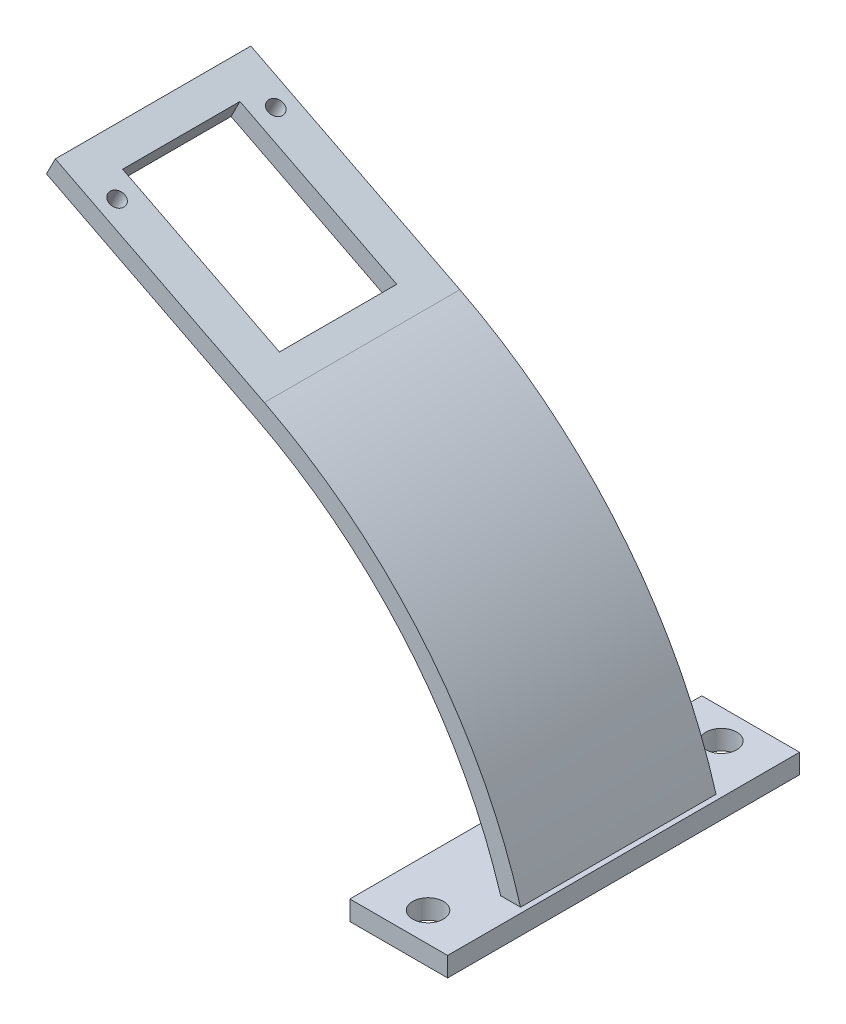
SolidWorks part; units mm, degrees
ref_plane "Front" through (0, 0, 0) normal (0, 0, 1) x (1, 0, 0)
ref_plane "Top" through (0, 0, 0) normal (0, 1, 0) x (1, 0, 0)
ref_plane "Right" through (0, 0, 0) normal (1, 0, 0) x (0, 0, -1)
sketch "Sketch1" plane through (0, 0, 0) normal (0, 0, 1) x (1, 0, 0)
  line L0 (-32.5783, 40.4088) -> (-59.7361, 54.2465)
  line L1 (-59.7361, 54.2465) -> (-58.583, 56.5096)
  line L2 (-58.583, 56.5096) -> (-31.4251, 42.672)
  line L3 (0, 0) -> (2.54, 0)
  line L4 (55, 0) -> (-55, 0) construction
  arc A0 (0, 0) -> (-32.5783, 40.4088) centre (-61.4067, -16.1701) ccw
  arc A1 (-31.4251, 42.672) -> (2.54, 0) centre (-61.2999, -15.9605) cw
  dimension "D3" = 63.5
  dimension "D4" = 27
  dimension "D1" = 2.54
  dimension "D2" = 2.54
  dimension "D5" = 30.48
  dimension "D6" = 30.48
  dimension "D7" = 42.672
extrude "Boss-Extrude1" add sketch "Sketch1" along normal blind 25.4
sketch "Sketch2" plane through (10.7842, 21.1653, 0) normal (0.454, 0.891, 0) x (0.891, -0.454, 0)
  line L0 (-77.8527, -25.4) -> (-77.8527, 0) construction
  line L1 (-73.7379, -5.08) -> (-50.8779, -5.08)
  line L2 (-73.7379, -5.08) -> (-73.7379, -20.32)
  line L3 (-73.7379, -20.32) -> (-50.8779, -20.32)
  line L4 (-50.8779, -5.08) -> (-50.8779, -20.32)
  line L5 (-77.8527, 0) -> (-77.8527, -25.4) construction
  line L6 (-31.0803, 0) -> (31.0803, 0) construction
  line L7 (-77.8527, -12.7) -> (-50.8779, -12.7) construction
  line L8 (-47.3727, -25.4) -> (-77.8527, -25.4) construction
  circle A0 centre (-71.5027, -2.4168) radius 0.9995
  circle A1 centre (-71.5027, -23.034) radius 0.9995
  point P12 (-77.8527, -12.7)
  point P13 (-73.7379, -12.7)
  dimension "D4" = 1.999
  dimension "D6" = 20.6172
  dimension "D7" = 6.35
  dimension "D1" = 22.86
  dimension "D2" = 15.24
  dimension "D3" = 4.1148
  dimension "D5" = 2.366
extrude "Cut-Extrude1" cut sketch "Sketch2" against normal up to next
sketch "Sketch3" plane through (0, 0, 0) normal (0, 1, 0) x (1, 0, 0)
  line L0 (-31.0803, 0) -> (31.0803, 0) construction
  line L1 (2.54, -35.56) -> (-10.16, -35.56)
  line L2 (2.54, -35.56) -> (2.54, 10.16)
  line L3 (2.54, 10.16) -> (-10.16, 10.16)
  line L4 (-10.16, -35.56) -> (-10.16, 10.16)
  line L5 (-31.4251, -25.4) -> (2.54, -25.4) construction
  line L6 (2.54, -25.4) -> (2.54, 0) construction
  circle A0 centre (-3.81, 6.35) radius 2
  circle A1 centre (-3.81, -31.75) radius 2
  dimension "D1" = 4
  dimension "D2" = 4
  dimension "D5" = 6.35
  dimension "D3" = 38.1
  dimension "D4" = 6.35
  dimension "D6" = 10.16
  dimension "D7" = 10.16
  dimension "D8" = 12.7
extrude "Boss-Extrude2" add sketch "Sketch3" along normal blind 2.54
